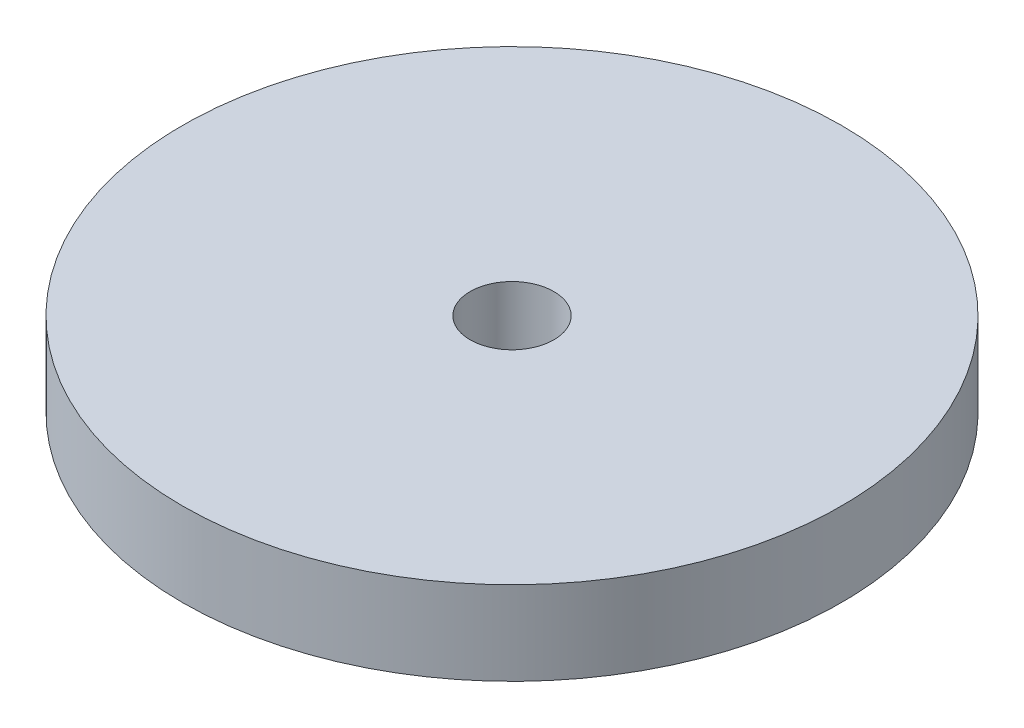
SolidWorks part; units mm, degrees
ref_plane "Plan de face" through (0, 0, 0) normal (0, 0, 1) x (1, 0, 0)
ref_plane "Plan de dessus" through (0, 0, 0) normal (0, 1, 0) x (1, 0, 0)
ref_plane "Plan de droite" through (0, 0, 0) normal (1, 0, 0) x (0, 0, -1)
sketch "Esquisse1" plane through (0, 0, 0) normal (0, 1, 0) x (1, 0, 0)
  circle A0 centre (0, 0) radius 25
  dimension "D1" = 50
extrude "Boss.-Extru.1" add sketch "Esquisse1" along normal blind 6.35
sketch "Esquisse2" plane through (0, 6.35, 0) normal (0, 1, 0) x (1, 0, 0)
  circle A0 centre (0, 0) radius 3.175
  dimension "D1" = 6.35
extrude "Enlèv. mat.-Extru.1" cut sketch "Esquisse2" against normal up to next
